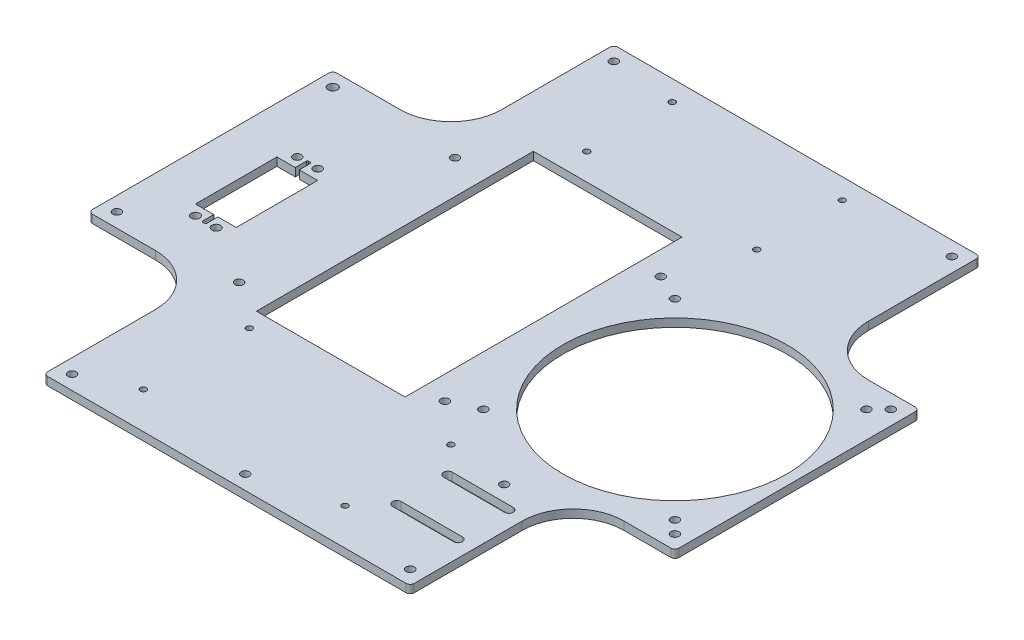
SolidWorks part; units mm, degrees
ref_plane "前视基准面" through (0, 0, 0) normal (0, 0, 1) x (1, 0, 0)
ref_plane "上视基准面" through (0, 0, 0) normal (0, 1, 0) x (1, 0, 0)
ref_plane "右视基准面" through (0, 0, 0) normal (1, 0, 0) x (0, 0, -1)
other "Configuration Table"
sketch "草图1" plane through (0, 0, 0) normal (0, 1, 0) x (1, 0, 0)
  line L0 (0, 203.4681) -> (0, -172.537) construction
  line L1 (-90, -140) -> (90, -140)
  line L3 (-90, 140) -> (90, 140)
  line L4 (140, -60) -> (140, 60)
  line L5 (-180.3272, 0) -> (180.5428, 0) construction
  line L6 (-140, 60) -> (-148, 60)
  line L7 (-148, 60) -> (-148, -60)
  line L8 (-148, -60) -> (-140, -60)
  line L9 (90, -140) -> (90, -60) construction
  line L13 (90, 140) -> (90, 60)
  line L14 (90, 60) -> (140, 60)
  line L15 (140, -60) -> (90, -60)
  line L16 (90, -60) -> (90, -140)
  line L17 (-140, -60) -> (-90, -60)
  line L18 (-90, -60) -> (-90, -140)
  line L19 (-140, 60) -> (-90, 60)
  line L20 (-90, 60) -> (-90, 140)
  point P0 (0, 0)
  dimension "D2" = 280
  dimension "D3" = 80
  dimension "D4" = 50
  dimension "D5" = 50
  dimension "D6" = 8
extrude "凸台-拉伸1" add sketch "草图1" along normal blind 4
sketch "草图3" plane through (0, 4, 0) normal (0, 1, 0) x (1, 0, 0)
  line L3 (-90, 140) -> (-90, 60) construction
  line L4 (90, 140) -> (-90, 140) construction
  line L5 (90, 60) -> (90, 140) construction
  line L6 (140, -60) -> (140, 60) construction
  line L7 (140, 60) -> (90, 60) construction
  line L8 (90, -60) -> (140, -60) construction
  line L9 (90, -140) -> (90, -60) construction
  line L10 (-90, -140) -> (90, -140) construction
  line L11 (-90, -60) -> (-90, -140) construction
  line L12 (80, 0) -> (80, 79.1014) construction
  line L13 (-6.3165, 0) -> (80, 0) construction
  line L14 (80, 0) -> (14.4577, 65.5423) construction
  line L15 (-90, 60) -> (-148, 60) construction
  line L16 (-148, 60) -> (-148, -60) construction
  line L17 (-148, -60) -> (-90, -60) construction
  circle A2 centre (-83, -133) radius 2
  circle A3 centre (83, -133) radius 2
  circle A4 centre (-83, 133) radius 2
  circle A5 centre (83, 133) radius 2
  circle A6 centre (133, 53) radius 2
  circle A7 centre (133, -53) radius 2
  circle A17 centre (80, 0) radius 66.5 construction
  circle A18 centre (32.9774, 47.0226) radius 2
  circle A19 centre (127.0226, 47.0226) radius 2
  circle A20 centre (127.0226, -47.0226) radius 2
  circle A21 centre (32.9774, -47.0226) radius 2
  circle A22 centre (-141, 53) radius 2.297
  circle A23 centre (-141, -53) radius 2
  circle A24 centre (20, -53) radius 2
  circle A25 centre (20, 53) radius 2
  circle A26 centre (-81, 53) radius 2
  circle A27 centre (-81, -53) radius 2
  circle A28 centre (70, -73.8542) radius 2
  circle A29 centre (2, -133) radius 2
  point P62 (80, 0)
  dimension "D3" = 7
  dimension "D4" = 7
  dimension "D5" = 7
  dimension "D6" = 7
  dimension "D7" = 7
  dimension "D8" = 7
  dimension "D9" = 7
  dimension "D10" = 7
  dimension "D11" = 7
  dimension "D12" = 7
  dimension "D13" = 7
  dimension "D14" = 7
  dimension "D15" = 7
  dimension "D16" = 7
  dimension "D17" = 7
  dimension "D18" = 133
  dimension "D20" = 4
  dimension "D22" = 7
  dimension "D23" = 4
  dimension "D24" = 4
  dimension "D25" = 4
  dimension "D26" = 113
  dimension "D27" = 113
  dimension "D28" = 106
  dimension "D29" = 4
  dimension "D30" = 60
  dimension "D31" = 4
  dimension "D32" = 60
  dimension "D33" = 4
  dimension "D34" = 20
  dimension "D35" = 4
  dimension "D36" = 7
  dimension "D37" = 81
  dimension "D19" = 45
  dimension "D21" = 4
extrude "切除-拉伸2" cut sketch "草图3" against normal through all both
sketch "草图4" plane through (0, 4, 0) normal (0, 1, 0) x (1, 0, 0)
  circle A0 centre (80, 0) radius 55
  dimension "D1" = 110
  dimension "D2" = 80
extrude "切除-拉伸3" cut sketch "草图4" against normal blind 10
sketch "草图5" plane through (0, 4, 0) normal (0, 1, 0) x (1, 0, 0)
  line L0 (-105.0538, 9.6251) -> (-105.0538, -30.3749)
  line L1 (-105.0538, -30.3749) -> (-114.0538, -30.3749)
  line L2 (-125.0538, -30.3749) -> (-125.0538, 9.6251)
  line L3 (-105.0538, 9.6251) -> (-114.0538, 9.6251)
  line L4 (-116.0538, 15.1251) -> (-115.5538, 15.6251)
  line L5 (-115.0538, 9.6251) -> (-115.0538, -33.8071) construction
  line L6 (-116.0538, 9.6251) -> (-116.0538, 15.1251)
  line L7 (-115.5538, 15.6251) -> (-114.5538, 15.6251)
  line L8 (-114.0538, 15.1251) -> (-114.0538, 9.6251)
  line L9 (-114.5538, 15.6251) -> (-114.0538, 15.1251)
  line L10 (-116.0538, 9.6251) -> (-125.0538, 9.6251)
  line L11 (-116.0538, -30.3749) -> (-116.0538, -35.8749)
  line L12 (-115.5538, -36.3749) -> (-114.5538, -36.3749)
  line L13 (-114.0538, -35.8749) -> (-114.0538, -30.3749)
  line L14 (-116.0538, -30.3749) -> (-125.0538, -30.3749)
  line L15 (-116.0538, -35.8749) -> (-115.5538, -36.3749)
  line L16 (-114.5538, -36.3749) -> (-114.0538, -35.8749)
  circle A0 centre (-110.0538, 14.6251) radius 2
  circle A1 centre (-120.0538, 14.6251) radius 2
  circle A2 centre (-120.0538, -35.3749) radius 2.1
  circle A3 centre (-109.8606, -35.3749) radius 2.1
  point P17 (-116.0538, 15.6251)
  point P19 (-114.0538, 15.6251)
  point P23 (-116.0538, -36.3749)
  point P25 (-114.0538, -36.3749)
  dimension "D1" = 4
  dimension "D2" = 4
  dimension "D6" = 5
  dimension "D7" = 5
  dimension "D11" = 5
  dimension "D14" = 5
  dimension "D15" = 4.2
  dimension "D18" = 4.2
  dimension "D19" = 5
  dimension "D20" = 5
  dimension "D3" = 6
  dimension "D4" = 2
  dimension "D5" = 1
  dimension "D8" = 5
  dimension "D12" = 6
  dimension "D13" = 2
extrude "切除-拉伸4" cut sketch "草图5" against normal through all
sketch "草图6" plane through (0, 4, 0) normal (0, 1, 0) x (1, 0, 0)
  line L0 (90, -140) -> (90, -60) construction
  line L1 (-90, -140) -> (90, -140) construction
  circle A0 centre (40, -122) radius 1.5
  circle A1 centre (40, -70) radius 1.5
  circle A2 centre (-59, -122) radius 1.5
  circle A3 centre (-59, -70) radius 1.5
  dimension "D1" = 3
  dimension "D2" = 3
  dimension "D3" = 3
  dimension "D4" = 3
  dimension "D8" = 99
  dimension "D9" = 50
  dimension "D10" = 18
  dimension "D5" = 99
  dimension "D6" = 52
  dimension "D7" = 52
extrude "切除-拉伸5" cut sketch "草图6" against normal through all
sketch "草图7" plane through (0, 4, 0) normal (0, 1, 0) x (1, 0, 0)
  line L0 (82, -108.5) -> (52, -108.5) construction
  line L1 (82, -110.6) -> (52, -110.6)
  line L2 (82, -106.4) -> (52, -106.4)
  line L3 (82, -83.5) -> (52, -83.5) construction
  line L4 (82, -85.6) -> (52, -85.6)
  line L5 (82, -81.4) -> (52, -81.4)
  line L6 (36.5, -128.5) -> (36.5, -63.5) construction
  line L7 (90, -140) -> (90, -60) construction
  arc A0 (82, -110.6) -> (82, -106.4) centre (82, -108.5) ccw
  arc A1 (52, -106.4) -> (52, -110.6) centre (52, -108.5) ccw
  arc A2 (82, -85.6) -> (82, -81.4) centre (82, -83.5) ccw
  arc A3 (52, -81.4) -> (52, -85.6) centre (52, -83.5) ccw
  point P2 (67, -108.5)
  point P7 (67, -83.5)
  point P16 (36.5, -96)
  dimension "D3" = 2.1
  dimension "D4" = 2.1
  dimension "D1" = 25
  dimension "D2" = 12.5
  dimension "D5" = 8
  dimension "D6" = 30
  dimension "D7" = 30
  dimension "D8" = 8
extrude "切除-拉伸6" cut sketch "草图7" against normal through all
sketch "草图8" plane through (0, 4, 0) normal (0, 1, 0) x (1, 0, 0)
  line L0 (-148, 60) -> (-148, -60) construction
  line L1 (-64.5, 75) -> (8.5, 75)
  line L2 (-64.5, 75) -> (-64.5, -61)
  line L3 (-64.5, -61) -> (8.5, -61)
  line L4 (8.5, 75) -> (8.5, -61)
  line L5 (-64.5, 75) -> (8.5, -61) construction
  line L6 (-64.5, -61) -> (8.5, 75) construction
  line L7 (-90, -140) -> (90, -140) construction
  point P0 (-28, 7)
  dimension "D1" = 73
  dimension "D2" = 136
  dimension "D3" = 120
  dimension "D4" = 147
extrude "切除-拉伸7" cut sketch "草图8" against normal through all both
sketch "草图9" plane through (0, 4, 0) normal (0, 1, 0) x (1, 0, 0)
  line L0 (8.5, 75) -> (-64.5, 75) construction
  circle A0 centre (-51.3395, 88) radius 1.5
  circle A1 centre (-51.3395, 130) radius 1.5
  circle A2 centre (32.1605, 130) radius 1.4411
  circle A3 centre (32.1605, 88) radius 1.5
  dimension "D1" = 3
  dimension "D2" = 3
  dimension "D3" = 42
  dimension "D4" = 13
  dimension "D5" = 3
  dimension "D6" = 83.5
  dimension "D7" = 42
  dimension "D8" = 83.5
extrude "切除-拉伸8" cut sketch "草图9" against normal through all both
fillet "圆角1" radius 2 8 edges at (-148, 2, -60) (-148, 2, 60) (-90, 2, 140) (90, 2, 140) (140, 2, 60) (140, 2, -60) (-90, 2, -140) (90, 2, -140)
fillet "圆角2" radius 25 1 edges at (-90, 2, 60)
fillet "圆角3" radius 25 3 edges at (90, 2, 60) (90, 2, -60) (-90, 2, -60)
